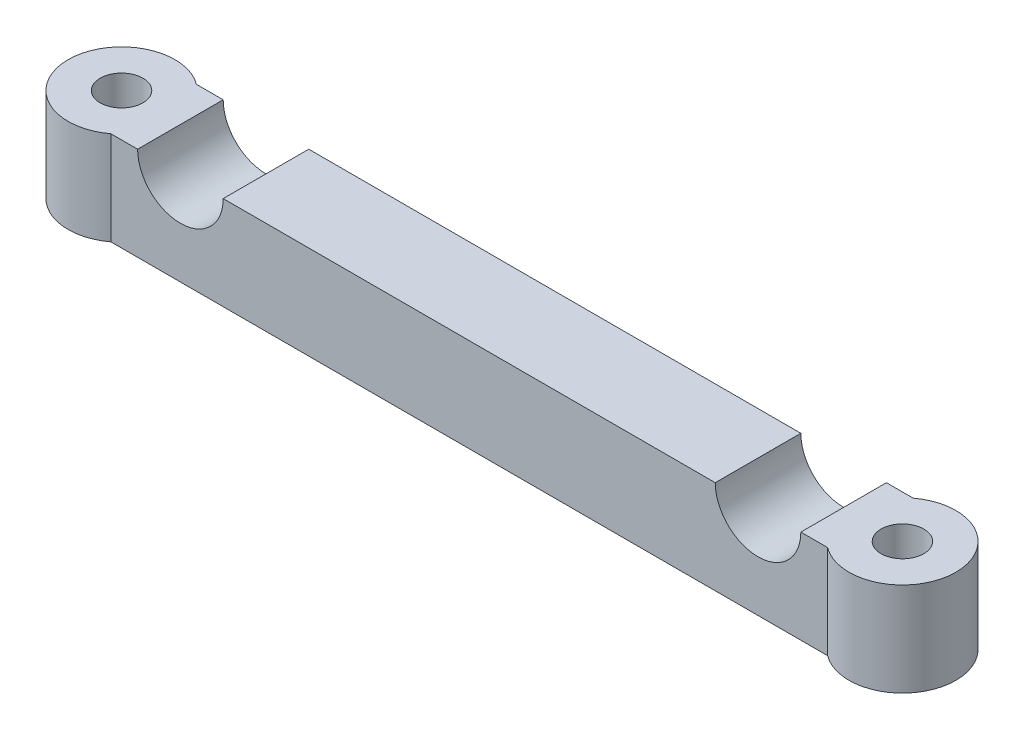
SolidWorks part; units mm, degrees
material "6061 Alloy"
ref_plane "Front Plane" through (0, 0, 0) normal (0, 0, 1) x (1, 0, 0)
ref_plane "Top Plane" through (0, 0, 0) normal (0, 1, 0) x (1, 0, 0)
ref_plane "Right Plane" through (0, 0, 0) normal (1, 0, 0) x (0, 0, -1)
sketch "Sketch1" plane through (0, 0, 0) normal (0, 1, 0) x (1, 0, 0)
  line L1 (-53.1812, 6.35) -> (53.1813, 6.35)
  line L3 (-53.1812, -6.35) -> (53.1813, -6.35)
  line L5 (-53.1812, 6.35) -> (53.1813, -6.35) construction
  line L6 (-53.1812, -6.35) -> (53.1813, 6.35) construction
  arc A0 (-53.1812, 6.35) -> (-53.1812, -6.35) centre (-57.9437, 0) ccw
  arc A1 (53.1813, 6.35) -> (53.1813, -6.35) centre (57.9438, 0) cw
  point P0 (0, 0)
  dimension "D3" = 7.9375
  dimension "D1" = 106.3625
  dimension "D2" = 12.7
extrude "Boss-Extrude1" add sketch "Sketch1" along normal blind 13.8989
sketch "Sketch2" plane through (0, 0, 6.35) normal (0, 0, 1) x (1, 0, 0)
  line L0 (-53.1812, 13.8989) -> (53.1813, 13.8989) construction
  line L2 (0, 13.8989) -> (0, 0) construction
  line L3 (-53.1812, 0) -> (53.1813, 0) construction
  line L4 (-49.2125, 13.8989) -> (-36.5125, 13.8989)
  line L5 (36.5125, 13.8989) -> (49.2125, 13.8989)
  arc A0 (-49.2125, 13.8989) -> (-36.5125, 13.8989) centre (-42.8625, 13.8989) ccw
  arc A1 (49.2125, 13.8989) -> (36.5125, 13.8989) centre (42.8625, 13.8989) cw
  dimension "D1" = 6.35
  dimension "D2" = 3.9688
extrude "Cut-Extrude1" cut sketch "Sketch2" against normal through all and the other way through all
hole_wizard "1/4 (0.25) Diameter Hole1" positions "Sketch4" profile "Sketch5" hole size "1/4" standard "ANSI Inch" end condition through all
sketch "Sketch4" plane through (0, 13.8989, 0) normal (0, 1, 0) x (1, 0, 0)
  point P0 (-57.9437, 0)
  point P3 (57.9438, 0)
sketch "Sketch5" plane through (-57.9437, 13.8989, 0) normal (1, 0, 0) x (0, 0, 1)
  line L0 (0, 0) -> (0, 13.8989)
  line L1 (0, 13.8989) -> (3.175, 13.8989)
  line L2 (3.175, 13.8989) -> (3.175, 0)
  line L5 (3.175, 0) -> (0, 0)
  line L11 (0, -6.35) -> (0, 107.95) construction
  dimension "Thru Hole Dia." = 6.35
  dimension "Thru Hole Depth" = 13.8989
